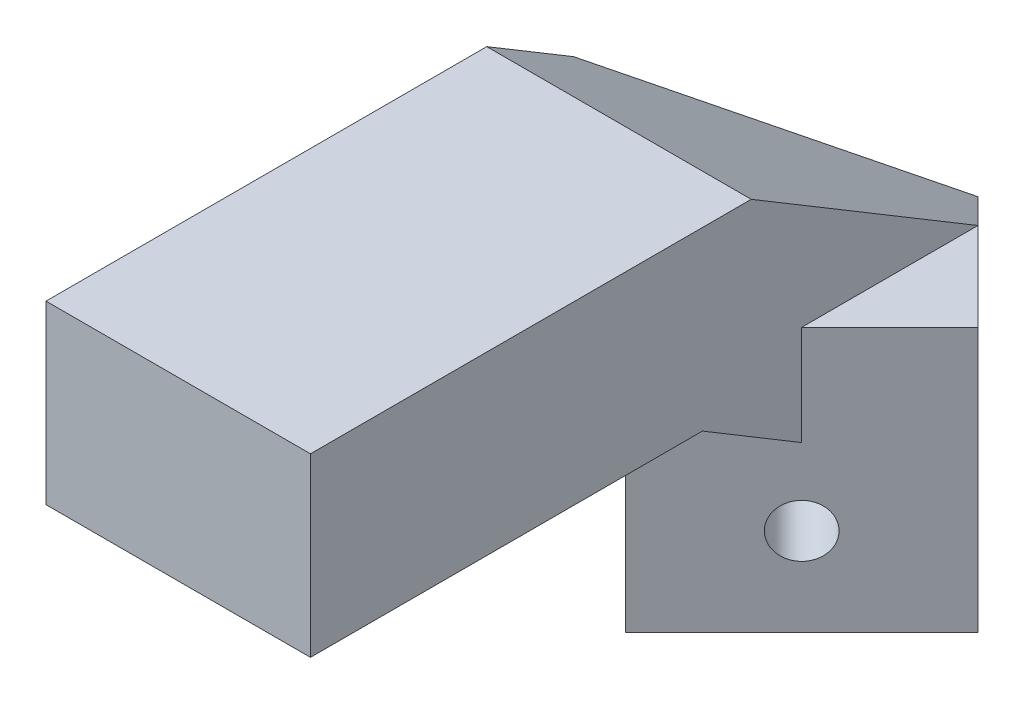
SolidWorks part; units mm, degrees
ref_plane "Alzado" through (0, 0, 0) normal (0, 0, 1) x (1, 0, 0)
ref_plane "Planta" through (0, 0, 0) normal (0, 1, 0) x (1, 0, 0)
ref_plane "Vista lateral" through (0, 0, 0) normal (1, 0, 0) x (0, 0, -1)
sketch "Croquis2" plane through (0, 0, 0) normal (1, 0, 0) x (0, 0, -1)
  line L0 (0, 0) -> (-50, 0)
  line L1 (-50, 0) -> (-75.7248, -15.4349)
  line L2 (-75.7248, -15.4349) -> (-75.7248, -45.4349)
  line L3 (0, -20) -> (-44.4603, -20)
  line L4 (-44.4603, -20) -> (-55.7248, -26.7587)
  line L5 (-55.7248, -26.7587) -> (-55.7248, -45.4349)
  line L6 (-75.7248, -45.4349) -> (-55.7248, -45.4349)
  line L7 (0, -20) -> (0, 0)
  dimension "D1" = 50
  dimension "D2" = 30
  dimension "D3" = 30
  dimension "D4" = 20
extrude "Saliente-Extruir2" add sketch "Croquis2" along normal blind 30
ref_plane "Plano1" through (-22.8624, 0, 22.8624) normal (-0.7071, 0, 0.7071) x (0.7071, 0, 0.7071)
sketch "Croquis3" plane through (-22.8624, 0, 22.8624) normal (-0.7071, 0, 0.7071) x (0.7071, 0, 0.7071)
  line L1 (81.8312, 10.6133) -> (21.2018, 10.6133)
  line L2 (81.8312, 10.6133) -> (81.8312, -50.3524)
  line L3 (81.8312, -50.3524) -> (21.2018, -50.3524)
  line L4 (21.2018, 10.6133) -> (21.2018, -50.3524)
extrude "Cortar-Extruir1" cut sketch "Croquis3" along normal blind 30
sketch "Croquis4" plane through (-22.8624, 0, 22.8624) normal (-0.7071, 0, 0.7071) x (0.7071, 0, 0.7071)
  circle A0 centre (60.6166, -34.2261) radius 3
  dimension "D1" = 6
extrude "Cortar-Extruir2" cut sketch "Croquis4" against normal through all
sketch "Croquis5" plane through (-22.8624, 0, 22.8624) normal (-0.7071, 0, 0.7071) x (0.7071, 0, 0.7071)
  line L1 (46.4744, -45.4349) -> (74.7587, -45.4349)
  line L2 (46.4744, -45.4349) -> (46.4744, -15.4349)
  line L3 (46.4744, -15.4349) -> (74.7587, -15.4349)
  line L4 (74.7587, -45.4349) -> (74.7587, -15.4349)
  line L5 (74.7587, -15.4349) -> (74.7587, -45.4349) construction
extrude "Saliente-Extruir3" add sketch "Croquis5" against normal up to vertex (14.1421 mm away)
sketch "Croquis6" plane through (-22.8624, 0, 22.8624) normal (-0.7071, 0, 0.7071) x (0.7071, 0, 0.7071)
  line L7 (32.3323, -20.7587) -> (46.4744, -26.7587)
  line L8 (46.4744, -26.7587) -> (46.4744, -45.4349)
  line L9 (46.4744, -45.4349) -> (74.7587, -45.4349)
  line L10 (74.7587, -45.4349) -> (74.7587, -15.4349)
  line L11 (74.7587, -15.4349) -> (38.3784, 0)
  line L12 (38.3784, 0) -> (32.3323, 0)
  line L13 (32.3323, 0) -> (32.3323, -20.7587)
  line L14 (32.3323, -20.7587) -> (46.4744, -26.7587)
  line L15 (46.4744, -26.7587) -> (46.4744, -45.4349)
  line L16 (46.4744, -45.4349) -> (74.7587, -45.4349)
  line L17 (74.7587, -45.4349) -> (74.7587, -15.4349)
  line L18 (74.7587, -15.4349) -> (38.3784, 0)
  line L19 (38.3784, 0) -> (32.3323, 0)
  line L20 (32.3323, 0) -> (32.3323, -20.7587)
  dimension "D1" = 0
extrude "Saliente-Extruir4" add sketch "Croquis6" along normal blind 10
sketch "Croquis7" plane through (0, 0, 0) normal (0, 1, 0) x (1, 0, 0)
  line L0 (0, 0) -> (0, -45.7248) construction
  line L1 (0, -42.9549) -> (-23.5817, -42.9549)
  line L2 (0, -42.9549) -> (0, -73.1611)
  line L3 (0, -73.1611) -> (-23.5817, -73.1611)
  line L4 (-23.5817, -42.9549) -> (-23.5817, -73.1611)
extrude "Cortar-Extruir3" cut sketch "Croquis7" against normal blind 60
sketch "Croquis8" plane through (-29.9335, 0, 29.9335) normal (-0.7071, 0, 0.7071) x (0.7071, 0, 0.7071)
  line L0 (60.6166, -45.4349) -> (60.6166, -35.4349) construction
  line L1 (46.4744, -45.4349) -> (74.7587, -45.4349) construction
  circle A0 centre (60.6166, -35.4349) radius 3
  dimension "D1" = 10
  dimension "D2" = 6
extrude "Cortar-Extruir4" cut sketch "Croquis8" against normal through all
ref_plane "Plano2" through (30, 0, 50) normal (-1, 0, 0) x (0, 0, 1)
sketch "Croquis10" plane through (0, 22.0588, 13.2353) normal (0, 0.8575, 0.5145) x (1, 0, 0)
  line L1 (47.0599, -40.39) -> (-32.0125, -40.39)
  line L2 (47.0599, -40.39) -> (47.0599, -96.7913)
  line L3 (47.0599, -96.7913) -> (-32.0125, -96.7913)
  line L4 (-32.0125, -40.39) -> (-32.0125, -96.7913)
extrude "Cortar-Extruir5" cut sketch "Croquis10" along normal blind 50
ref_plane "Plano3" through (0, 0, -5) normal (0, 0, -1) x (-1, 0, 0)
mirror "Simetría3" about plane through (0, 0, -5) normal (0, 0, -1) of bodies 109
sketch "Croquis11" plane through (0, -20, 0) normal (0, -1, 0) x (1, 0, 0)
  line L1 (-46.9944, 92.238) -> (88.9404, 92.238)
  line L2 (-46.9944, 92.238) -> (-46.9944, -5.9922)
  line L3 (-46.9944, -5.9922) -> (88.9404, -5.9922)
  line L4 (88.9404, 92.238) -> (88.9404, -5.9922)
extrude "Cortar-Extruir6" cut sketch "Croquis11" against normal blind 97 and the other way blind 66
sketch "Croquis12" plane through (-34.9335, 0, -34.9335) normal (-0.7071, 0, -0.7071) x (-0.7071, 0, 0.7071)
  line L1 (-81.8298, -45.4349) -> (-22.6614, -45.4349)
  line L2 (-81.8298, -45.4349) -> (-81.8298, 2.6805)
  line L3 (-81.8298, 2.6805) -> (-22.6614, 2.6805)
  line L4 (-22.6614, -45.4349) -> (-22.6614, 2.6805)
